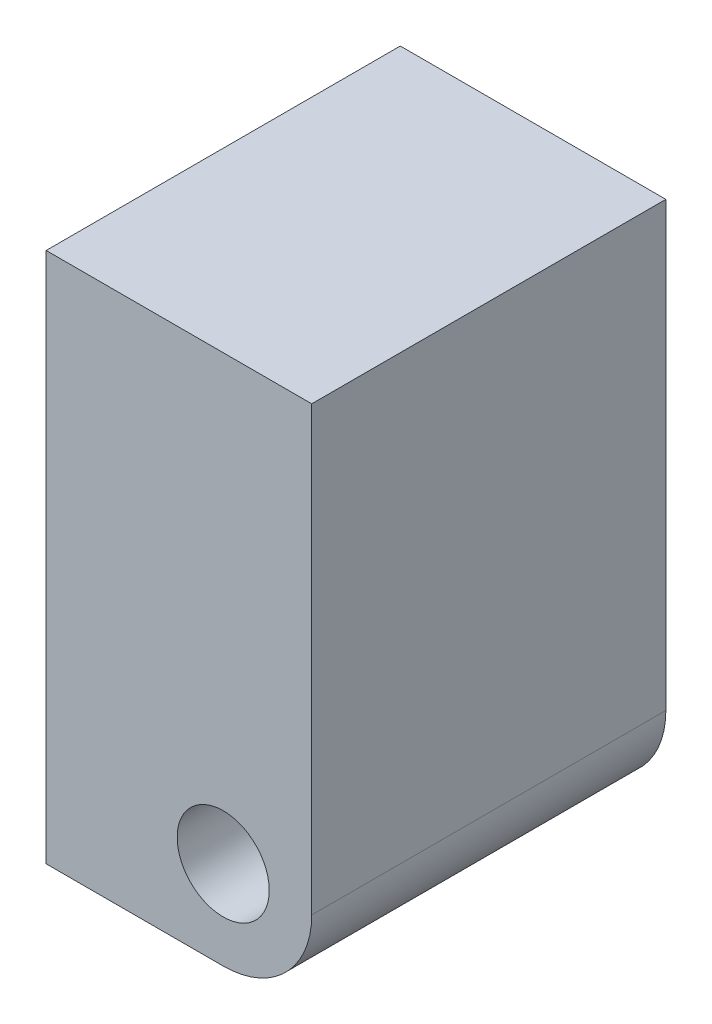
SolidWorks part; units mm, degrees
ref_plane "Alzado" through (0, 0, 0) normal (0, 0, 1) x (1, 0, 0)
ref_plane "Planta" through (0, 0, 0) normal (0, 1, 0) x (1, 0, 0)
ref_plane "Vista lateral" through (0, 0, 0) normal (1, 0, 0) x (0, 0, -1)
sketch "Croquis2" plane through (0, 0, 0) normal (0, 0, 1) x (1, 0, 0)
  line L0 (0, 0) -> (0, 25) construction
  line L2 (5, 0) -> (5, 25)
  line L3 (0, 25) -> (5, 25)
  line L9 (0, -5) -> (-10, -5)
  line L10 (-10, -5) -> (-10, 25)
  line L11 (-10, 25) -> (0, 25)
  circle A0 centre (0, 0) radius 2.6
  arc A1 (0, -5) -> (5, 0) centre (0, 0) ccw
  point P3 (0, 25)
  dimension "D1" = 25
  dimension "D2" = 5.2
  dimension "D3" = 5
  dimension "D4" = 10
extrude "Saliente-Extruir2" add sketch "Croquis2" along normal blind 20
